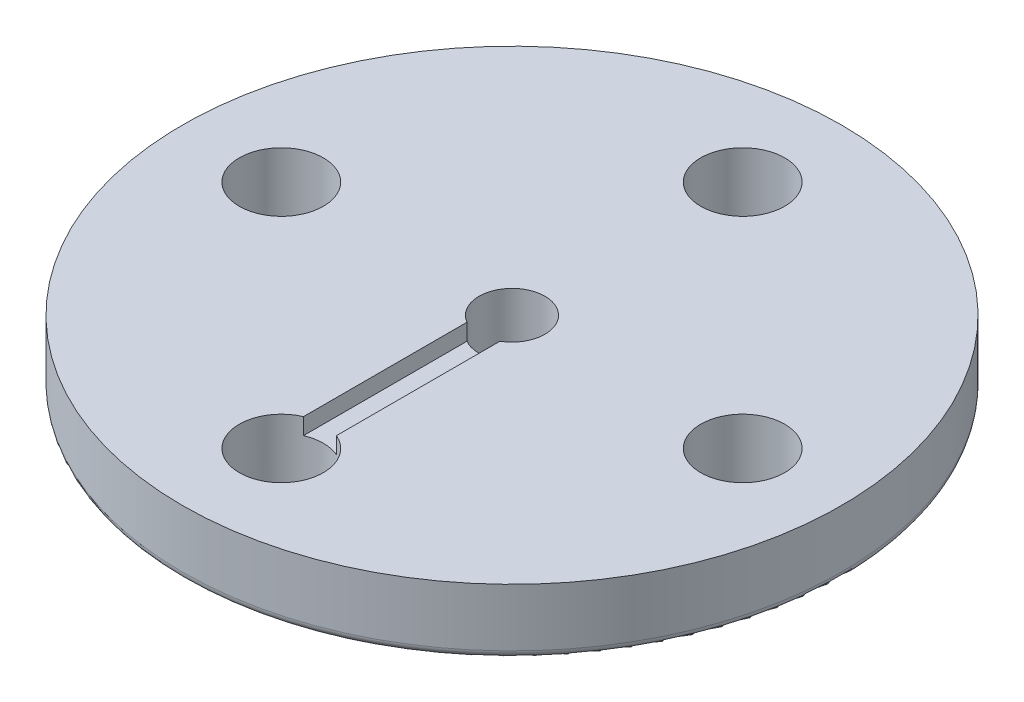
SolidWorks part; units mm, degrees
material "ABS"
ref_plane "Front Plane" through (0, 0, 0) normal (0, 0, 1) x (1, 0, 0)
ref_plane "Top Plane" through (0, 0, 0) normal (0, 1, 0) x (1, 0, 0)
ref_plane "Right Plane" through (0, 0, 0) normal (1, 0, 0) x (0, 0, -1)
sketch "Sketch1" plane through (0, 0, 0) normal (0, 1, 0) x (1, 0, 0)
  circle A0 centre (0, 0) radius 10
  dimension "D1" = 20
extrude "Boss-Extrude1" add sketch "Sketch1" along normal blind 2
sketch "Sketch2" plane through (0, 0, 0) normal (0, 1, 0) x (1, 0, 0)
  circle A0 centre (0, 0) radius 4.5
  dimension "D1" = 9
extrude "Boss-Extrude2" add sketch "Sketch2" against normal blind 2.5
sketch "Sketch3" plane through (0, 0, 0) normal (0, 1, 0) x (1, 0, 0)
  line L0 (0, 16.6668) -> (0, -17.2828) construction
  line L1 (-21.9372, 0) -> (30.2192, 0) construction
  line L2 (-7, 16.6668) -> (-7, -16.6668) construction
  line L3 (-15.9139, 7) -> (17.4197, 7) construction
  circle A0 centre (0, 7) radius 1.275
  circle A1 centre (-7, 0) radius 1.275
  circle A2 centre (0, -7) radius 1.275
  circle A3 centre (7, 0) radius 1.275
  dimension "D3" = 2.55
  dimension "D4" = 2.55
  dimension "D1" = 7
  dimension "D2" = 7
extrude "Cut-Extrude1" cut sketch "Sketch3" along normal through all
cosmetic thread "Cosmetic Thread1" parameters "D2"=2.87
cosmetic thread "Cosmetic Thread2" parameters "D2"=2.87
cosmetic thread "Cosmetic Thread3" parameters "D2"=2.87
cosmetic thread "Cosmetic Thread4" parameters "D2"=2.87
fillet "Fillet1" radius 0.25 1 edges at (0, 0, 10)
sketch "Sketch6" plane through (0, 2, 0) normal (0, 1, 0) x (1, 0, 0)
  circle A0 centre (0, 0) radius 1
  dimension "D1" = 2
extrude "Cut-Extrude2" cut sketch "Sketch6" against normal through all
sketch "Sketch7" plane through (0, -2.5, 0) normal (0, -1, 0) x (1, 0, 0)
  circle A0 centre (0, 0) radius 2.9
  dimension "D1" = 5.8
extrude "Cut-Extrude3" cut sketch "Sketch7" against normal blind 2.5
sketch3d "3DSketch1"
  line L0 (0, 0, 0) -> (0, -47.4119, 0) construction
sketch "Sketch8" plane through (0, -2.5, 0) normal (0, -1, 0) x (1, 0, 0)
  line L1 (-2.3524, -1.0465) -> (-2.7456, -0.9337)
  line L2 (-2.3524, -1.0465) -> (-2.5319, -1.4141)
  arc A1 (-2.7456, -0.9337) -> (-2.5319, -1.4141) centre (0, 0) ccw
  circle A4 centre (0, 0) radius 2.9 construction
  dimension "D4" = 0.409
  dimension "D3" = 5.8
  dimension "D1" = 80
  dimension "D2" = 0.5258
extrude "Boss-Extrude4" add sketch "Sketch8" against normal blind 2.5
pattern_circular "CirPattern1" count 26 over 360 about axis through (0, 0, 0) along (0, 1, 0) of "Boss-Extrude4"
sketch "Sketch9" plane through (0, 2, 0) normal (0, 1, 0) x (1, 0, 0)
  line L0 (0, 0) -> (0, -7)
  line L1 (-0.5, 0) -> (-0.5, -7)
  line L2 (0.5, 0) -> (0.5, -7)
  line L3 (-0.5, -7) -> (0.5, -7)
  line L4 (-0.5, 0) -> (0.5, 0)
  circle A1 centre (0, 0) radius 10
  circle A2 centre (0, 0) radius 10
  circle A3 centre (7, 0) radius 1.275
  circle A4 centre (7, 0) radius 1.275
  circle A5 centre (0, -7) radius 1.275
  circle A6 centre (0, -7) radius 1.275
  circle A7 centre (-7, 0) radius 1.275
  circle A8 centre (-7, 0) radius 1.275
  circle A9 centre (0, 0) radius 1
  circle A10 centre (0, 0) radius 1
  circle A11 centre (0, 7) radius 1.275
  circle A12 centre (0, 7) radius 1.275
  dimension "D7" = 0.5
  dimension "D1" = 0
  dimension "D2" = 0
  dimension "D3" = 0
  dimension "D4" = 0
  dimension "D5" = 0
  dimension "D6" = 0
  dimension "D8" = 0.5
extrude "Cut-Extrude4" cut sketch "Sketch9" against normal blind 0.5 contours L1 L3 L2 L4
